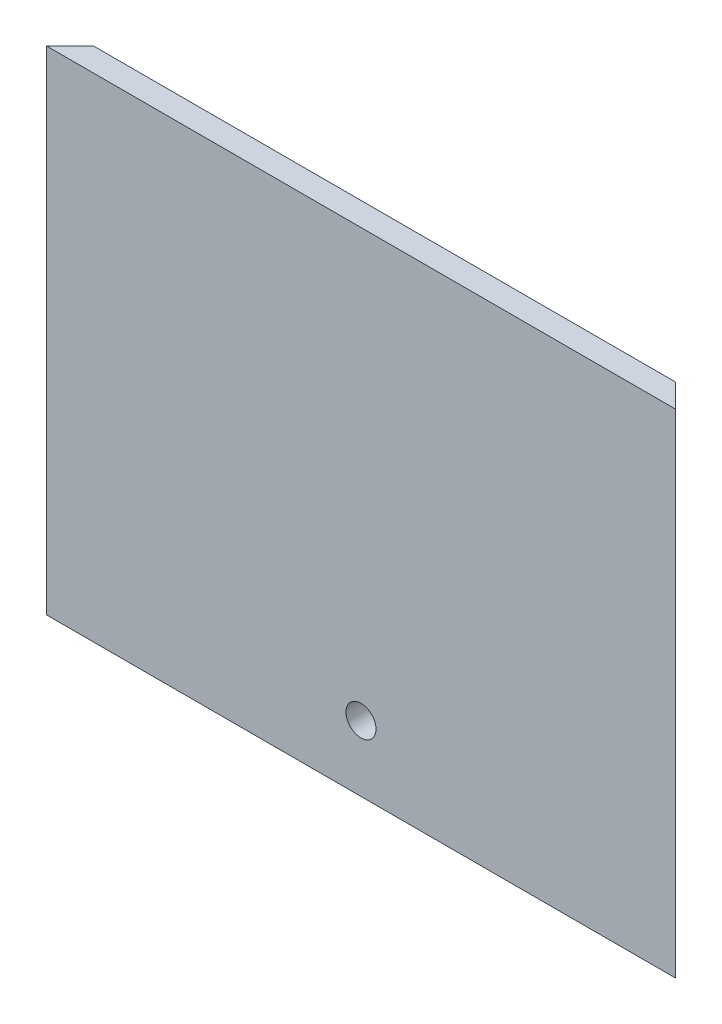
SolidWorks part; units mm, degrees
ref_plane "Front Plane" through (0, 0, 0) normal (0, 0, 1) x (1, 0, 0)
ref_plane "Top Plane" through (0, 0, 0) normal (0, 1, 0) x (1, 0, 0)
ref_plane "Right Plane" through (0, 0, 0) normal (1, 0, 0) x (0, 0, -1)
sketch "Sketch2" plane through (0, 0, 0) normal (0, 1, 0) x (1, 0, 0)
  line L0 (-33.5, -1.25) -> (-31, 1.25)
  line L1 (33.5, -1.25) -> (-33.5, -1.25)
  line L2 (33.5, -1.25) -> (33.5, 1.25)
  line L3 (33.5, 1.25) -> (-33.5, 1.25)
  line L4 (-33.5, -1.25) -> (-33.5, 1.25)
  line L5 (33.5, -1.25) -> (-33.5, 1.25) construction
  line L6 (33.5, 1.25) -> (-33.5, -1.25) construction
  line L7 (33.5, -1.25) -> (31, 1.25)
  point P0 (0, 0)
  dimension "D1" = 67
  dimension "D2" = 2.5
  dimension "D3" = 2.5
extrude "Boss-Extrude1" add sketch "Sketch2" along normal blind 52.5 contours L1 L7 L3 L0
sketch "Sketch3" plane through (0, 0, 1.25) normal (0, 0, 1) x (1, 0, 0)
  line L0 (0, 0) -> (0, 52.5) construction
  line L1 (33.5, 52.5) -> (-33.5, 52.5) construction
  line L2 (33.5, 0) -> (-33.5, 0) construction
  circle A0 centre (0, 7) radius 1.6
  dimension "D1" = 3.2
  dimension "D2" = 7
extrude "Cut-Extrude1" cut sketch "Sketch3" against normal through all contours A0 L0 | L0 A0
